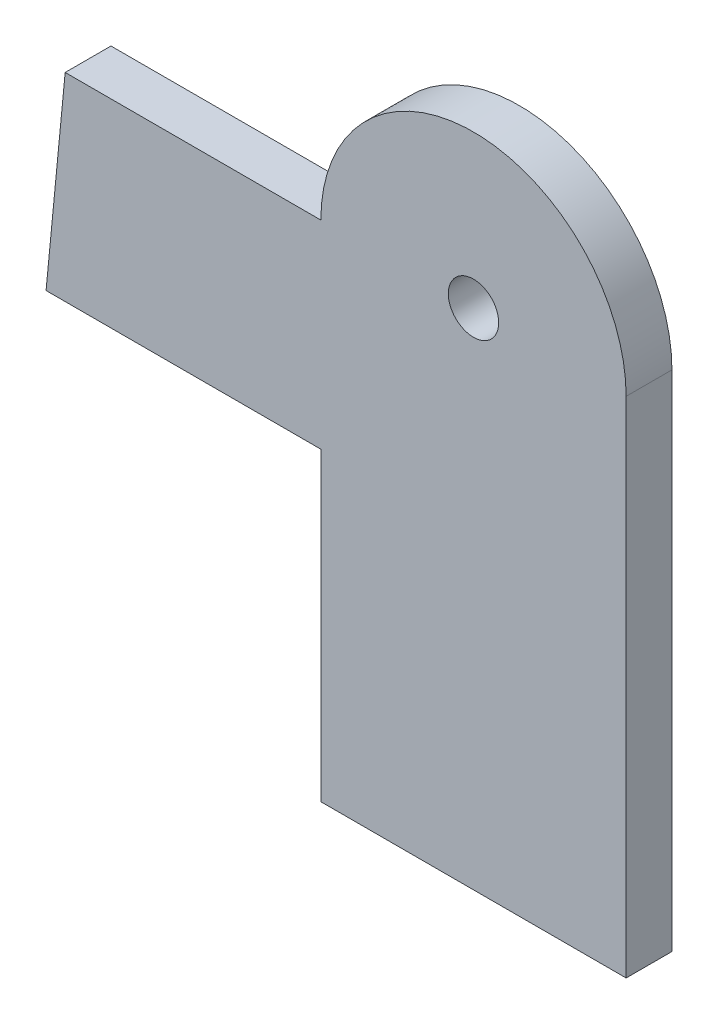
SolidWorks part; units mm, degrees
material "Thornel Mat VMA"
ref_plane "前视基准面" through (0, 0, 0) normal (0, 0, 1) x (1, 0, 0)
ref_plane "上视基准面" through (0, 0, 0) normal (0, 1, 0) x (1, 0, 0)
ref_plane "右视基准面" through (0, 0, 0) normal (1, 0, 0) x (0, 0, -1)
sketch "草图1" plane through (0, 0, 0) normal (0, 0, 1) x (1, 0, 0)
  line L0 (0, 0) -> (20, 0)
  line L1 (20, 0) -> (20, 33)
  line L2 (0, 33) -> (0, 0)
  arc A0 (20, 33) -> (0, 33) centre (10, 33) ccw
  circle A1 centre (10, 33) radius 1.65
  dimension "D1" = 3.3
  dimension "D2" = 20
  dimension "D3" = 33
extrude "凸台-拉伸1" add sketch "草图1" along normal blind 3
sketch "草图5" plane through (0, 0, 0) normal (0, 0, -1) x (-1, 0, 0)
  line L0 (0, 33) -> (0, 20)
  line L1 (0, 33) -> (0, 0) construction
  line L2 (0, 20) -> (18, 20)
  line L3 (18, 20) -> (16.7482, 33)
  line L4 (16.7482, 33) -> (0, 33)
  dimension "D1" = 84.5
  dimension "D2" = 18
  dimension "D3" = 13
extrude "凸台-拉伸2" add sketch "草图5" against normal up to surface (3 mm away) up to face at (10, 19, 3)
